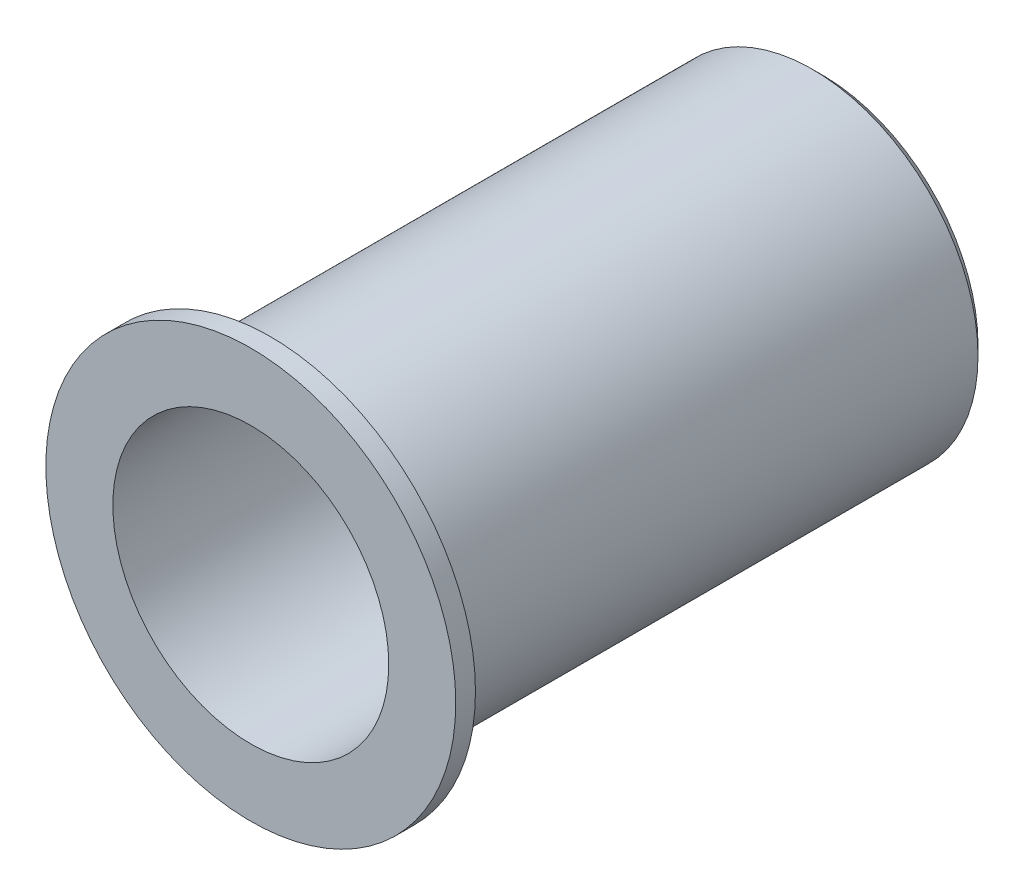
SolidWorks part; units mm, degrees
ref_plane "前视基准面" through (0, 0, 0) normal (0, 0, 1) x (1, 0, 0)
ref_plane "上视基准面" through (0, 0, 0) normal (0, 1, 0) x (1, 0, 0)
ref_plane "右视基准面" through (0, 0, 0) normal (1, 0, 0) x (0, 0, -1)
sketch "草图1" plane through (0, 0, 0) normal (0, 0, 1) x (1, 0, 0)
  circle A0 centre (0, 0) radius 8.4
  dimension "D1" = 16.8
extrude "凸台-拉伸1" add sketch "草图1" along normal blind 28
sketch "草图2" plane through (0, 0, 28) normal (0, 0, 1) x (1, 0, 0)
  circle A0 centre (0, 0) radius 7
extrude "切除-拉伸3" cut sketch "草图2" against normal blind 23
sketch "草图3" plane through (0, 0, 0) normal (0, 0, -1) x (-1, 0, 0)
  circle A0 centre (0, 0) radius 7 construction
  circle A1 centre (0, 0) radius 5
  circle A3 centre (0, 0) radius 7
  point P2 (0, 5)
  point P7 (4.3301, -2.5)
  point P8 (-4.3301, -2.5)
  point P9 (0, 0)
  dimension "D1" = 10
  dimension "D2" = 3
hole_wizard "M4 螺纹孔1" positions "草图8" profile "草图9" tap size "M4" standard "GB" end condition through all
sketch "草图8" plane through (0, 0, 0) normal (0, 0, -1) x (-1, 0, 0)
  point P0 (0, 5)
  point P3 (0, 0)
  point P6 (-4.3301, -2.5)
  point P9 (4.3301, -2.5)
sketch "草图9" plane through (0, 5, 0) normal (1, 0, 0) x (0, 1, 0)
  line L0 (0, 0) -> (0, 28)
  line L1 (0, 28) -> (1.65, 28)
  line L2 (1.65, 28) -> (1.65, 0)
  line L5 (1.65, 0) -> (0, 0)
  line L11 (0, -6.35) -> (0, 107.95) construction
  dimension "通孔螺纹孔钻头直径" = 3.3
  dimension "通孔螺纹孔钻头深度" = 28
cosmetic thread "孔螺蚊线5" parameters "D2"=4
cosmetic thread "孔螺蚊线6" parameters "D2"=4
cosmetic thread "孔螺蚊线7" parameters "D2"=4
cosmetic thread "孔螺蚊线8" parameters "D2"=4
sketch "草图10" plane through (0, 0, 28) normal (0, 0, 1) x (1, 0, 0)
  circle A0 centre (0, 0) radius 10.4
  circle A1 centre (0, 0) radius 8.4
  circle A2 centre (0, 0) radius 8.4
  circle A3 centre (0, 0) radius 7 construction
  circle A4 centre (0, 0) radius 7
  circle M2 centre (0, 0) radius 7
  circle M3 centre (0, 0) radius 8.4
  dimension "D1" = 0
  dimension "D2" = 2
extrude "凸台-拉伸4" add sketch "草图10" along normal blind 1 contours A0 M3 | M3 M2
chamfer "倒角1" distance 0.5 angle 45 1 edges at (8.4, 0, 0)
